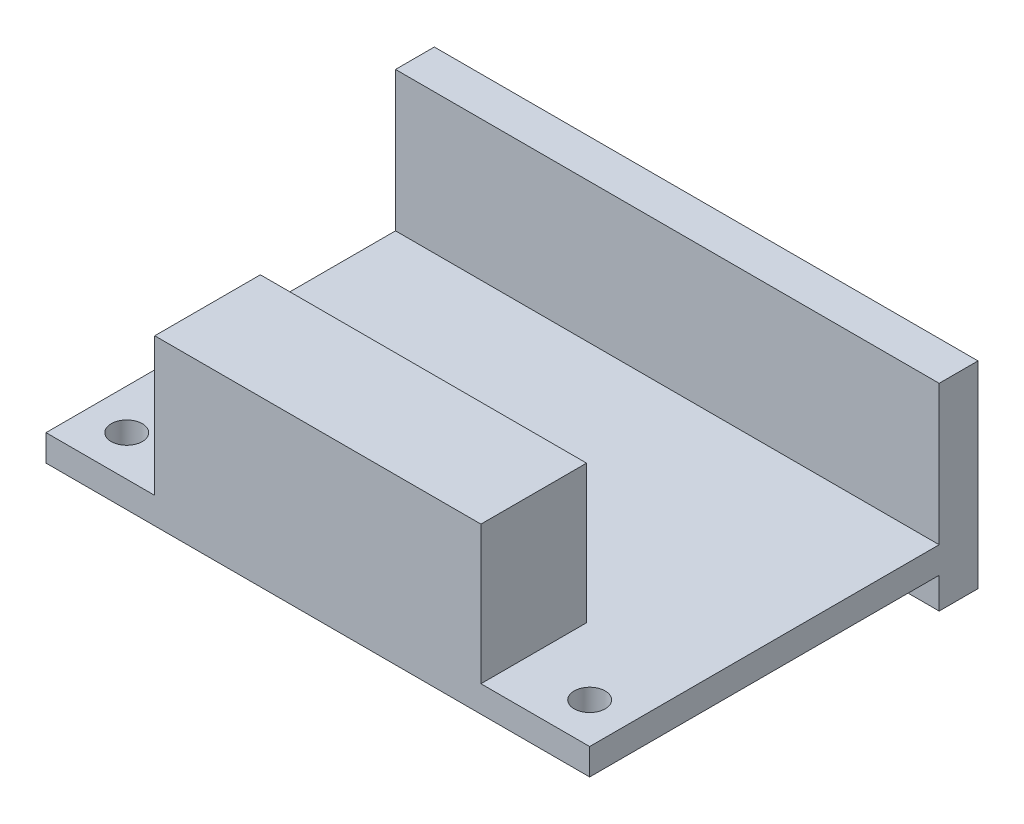
SolidWorks part; units mm, degrees
ref_plane "Front" through (0, 0, 0) normal (0, 0, 1) x (1, 0, 0)
ref_plane "Top" through (0, 0, 0) normal (0, 1, 0) x (1, 0, 0)
ref_plane "Right" through (0, 0, 0) normal (1, 0, 0) x (0, 0, -1)
sketch "Sketch1" plane through (0, 0, 0) normal (0, 1, 0) x (1, 0, 0)
  line L1 (-17.5, -12.5) -> (17.5, -12.5)
  line L2 (-17.5, -12.5) -> (-17.5, 12.5)
  line L3 (-17.5, 12.5) -> (17.5, 12.5)
  line L4 (17.5, -12.5) -> (17.5, 12.5)
  line L5 (-17.5, -12.5) -> (17.5, 12.5) construction
  line L6 (-17.5, 12.5) -> (17.5, -12.5) construction
  point P0 (0, 0)
  dimension "D1" = 25
  dimension "D2" = 35
extrude "Boss-Extrude1" add sketch "Sketch1" along normal blind 1.7
sketch "Sketch2" plane through (0, 1.7, 0) normal (0, 1, 0) x (1, 0, 0)
  line L0 (-17.5, -12.5) -> (17.5, -12.5) construction
  line L1 (10.5, -12.5) -> (-10.5, -12.5)
  line L2 (10.5, -12.5) -> (10.5, -5.7)
  line L3 (10.5, -5.7) -> (-10.5, -5.7)
  line L4 (-10.5, -12.5) -> (-10.5, -5.7)
  point P6 (0, -12.5)
  point P7 (0, -12.5)
  dimension "D1" = 21
  dimension "D2" = 6.8
extrude "Boss-Extrude2" add sketch "Sketch2" along normal blind 8.9
sketch "Sketch3" plane through (0, 1.7, 0) normal (0, 1, 0) x (1, 0, 0)
  line L0 (17.5, -12.5) -> (17.5, 12.5) construction
  line L1 (-17.5, 12.5) -> (17.5, 12.5)
  line L2 (-17.5, 12.5) -> (-17.5, 10)
  line L3 (-17.5, 10) -> (17.5, 10)
  line L4 (17.5, 12.5) -> (17.5, 10)
  dimension "D1" = 2.5
extrude "Boss-Extrude3" add sketch "Sketch3" along normal blind 9
sketch "Sketch4" plane through (0, 0, 0) normal (0, -1, 0) x (1, 0, 0)
  line L0 (17.5, 12.5) -> (17.5, -12.5) construction
  line L1 (-17.5, -12.5) -> (17.5, -12.5)
  line L2 (-17.5, -12.5) -> (-17.5, -10)
  line L3 (-17.5, -10) -> (17.5, -10)
  line L4 (17.5, -12.5) -> (17.5, -10)
  line L5 (-17.5, 12.5) -> (17.5, 12.5) construction
  line L6 (-9.75, 9.5) -> (9.75, 9.5)
  line L7 (-9.75, 9.5) -> (-9.75, 7)
  line L8 (-9.75, 7) -> (9.75, 7)
  line L9 (9.75, 9.5) -> (9.75, 7)
  point P11 (0, 9.5)
  dimension "D1" = 2.5
  dimension "D2" = 3
  dimension "D3" = 2.5
  dimension "D4" = 19.5
extrude "Boss-Extrude4" add sketch "Sketch4" along normal blind 2
sketch "Sketch5" plane through (0, 1.7, 0) normal (0, 1, 0) x (1, 0, 0)
  line L0 (-15.9, -9.9) -> (-17.5, -9.9) construction
  line L1 (-17.5, 10) -> (-17.5, -12.5) construction
  line L2 (-14.9, -10.9) -> (-14.9, -12.5) construction
  line L3 (-17.5, -12.5) -> (-10.5, -12.5) construction
  line L4 (15.9, -9.9) -> (17.5, -9.9) construction
  line L5 (17.5, -12.5) -> (17.5, 10) construction
  circle A0 centre (14.9, -9.9) radius 1
  circle A1 centre (-14.9, -9.9) radius 1
  dimension "D1" = 2
  dimension "D2" = 1.6
extrude "Cut-Extrude1" cut sketch "Sketch5" against normal up to next
